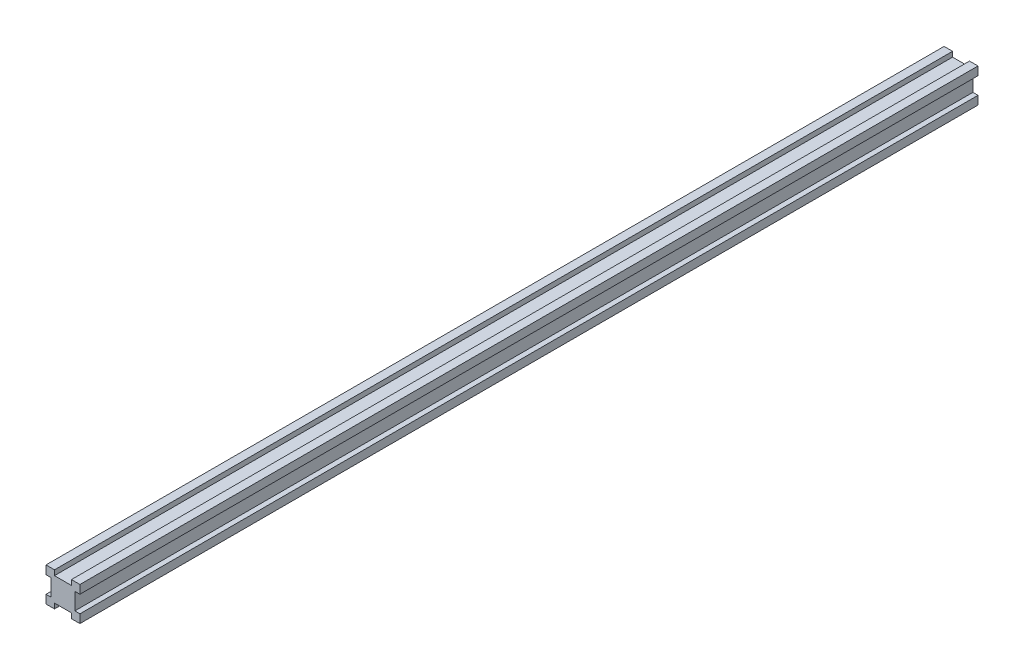
SolidWorks part; units mm, degrees
ref_plane "前视基准面" through (0, 0, 0) normal (0, 0, 1) x (1, 0, 0)
ref_plane "上视基准面" through (0, 0, 0) normal (0, 1, 0) x (1, 0, 0)
ref_plane "右视基准面" through (0, 0, 0) normal (1, 0, 0) x (0, 0, -1)
sketch "草图1" plane through (0, 0, 0) normal (0, 0, 1) x (1, 0, 0)
  line L0 (-5, 10) -> (-5, 7)
  line L1 (-10, -10) -> (10, -10)
  line L2 (-10, -10) -> (-10, -5)
  line L3 (-10, 10) -> (-5, 10)
  line L4 (10, -10) -> (10, -5)
  line L5 (-10, -10) -> (10, 10) construction
  line L6 (-10, 10) -> (10, -10) construction
  line L7 (-5, 7) -> (5, 7)
  line L8 (5, 7) -> (5, 10)
  line L9 (0, 0) -> (0, 17.8745) construction
  line L10 (7, 5) -> (7, -5)
  line L11 (10, 5) -> (7, 5)
  line L12 (7, -5) -> (10, -5)
  line L13 (5, -7) -> (-5, -7)
  line L14 (5, -10) -> (5, -7)
  line L15 (-5, -7) -> (-5, -10)
  line L16 (-7, -5) -> (-7, 5)
  line L17 (-10, -5) -> (-7, -5)
  line L18 (-7, 5) -> (-10, 5)
  line L19 (10, 5) -> (10, 10)
  line L20 (5, 10) -> (10, 10)
  line L21 (-10, 5) -> (-10, 10)
  point P0 (0, 0)
  point P27 (0, 0)
  dimension "D1" = 20
  dimension "D2" = 20
  dimension "D3" = 10
  dimension "D4" = 3
  dimension "D5" = 4
extrude "凸台-拉伸1" add sketch "草图1" along normal mid plane 530 contours L21 L18 L16 L17 L2 L1 L15 L13 L14 L4 L12 L10 L11 L19 L20 L8 L7 L0 L3
